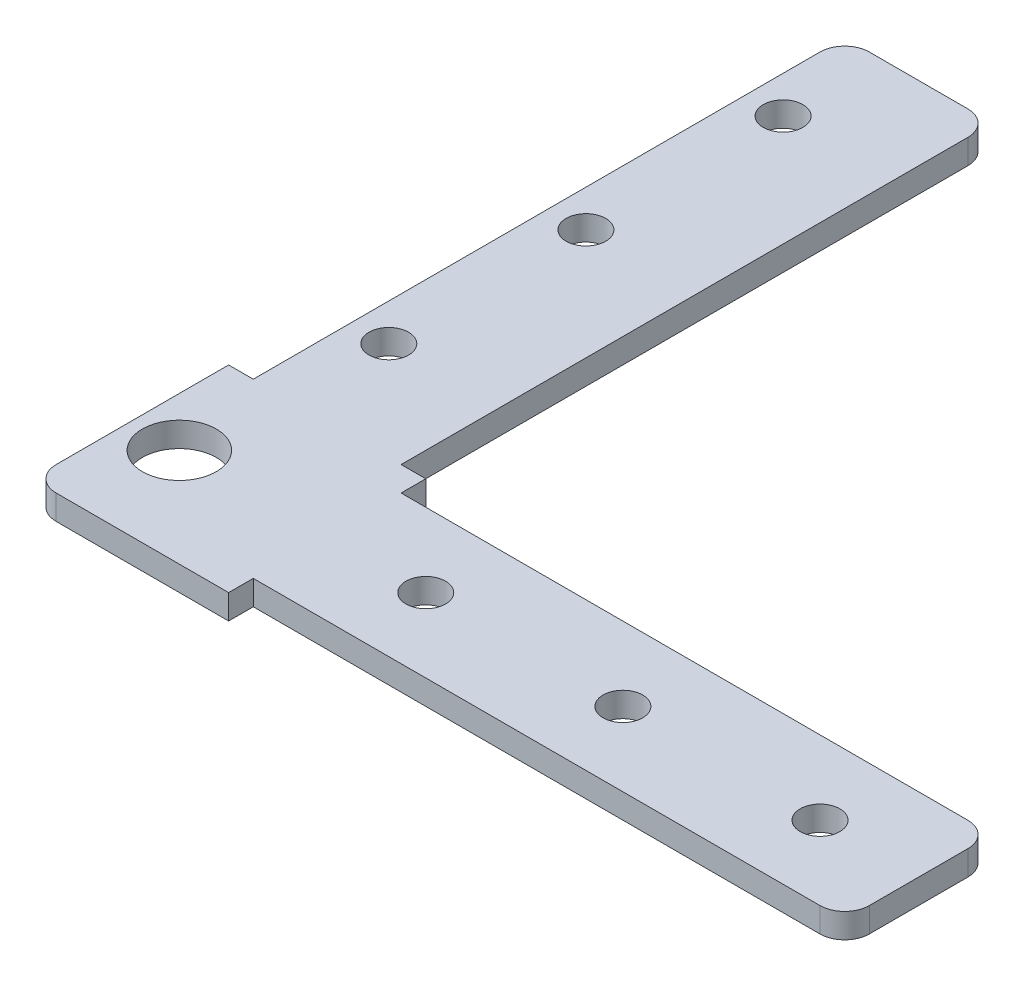
SolidWorks part; units mm, degrees
material "6061 Alloy"
ref_plane "Front" through (0, 0, 0) normal (0, 0, 1) x (1, 0, 0)
ref_plane "Top" through (0, 0, 0) normal (0, 1, 0) x (1, 0, 0)
ref_plane "Right" through (0, 0, 0) normal (1, 0, 0) x (0, 0, -1)
sketch "Sketch2" plane through (0, 0, 0) normal (0, 1, 0) x (1, 0, 0)
  line L0 (0, 0) -> (0, 25.4)
  line L1 (0, 25.4) -> (3.175, 25.4)
  line L2 (3.175, 25.4) -> (3.175, 101.6)
  line L3 (3.175, 101.6) -> (22.225, 101.6)
  line L4 (22.225, 101.6) -> (22.225, 25.4)
  line L5 (22.225, 25.4) -> (25.4, 25.4)
  line L6 (25.4, 25.4) -> (25.4, 22.225)
  line L7 (25.4, 22.225) -> (101.6, 22.225)
  line L8 (101.6, 22.225) -> (101.6, 3.175)
  line L9 (101.6, 3.175) -> (25.4, 3.175)
  line L10 (25.4, 3.175) -> (25.4, 0)
  line L11 (25.4, 0) -> (0, 0)
  dimension "D1" = 25.4
  dimension "D2" = 76.2
  dimension "D3" = 19.05
extrude "Boss-Extrude1" add sketch "Sketch2" along normal blind 3.175
hole_wizard "#10 Clearance Hole1" positions "Sketch3" profile "Sketch4" hole size "#10" standard "ANSI Inch" end condition through all
sketch "Sketch3" plane through (0, 3.175, 0) normal (0, 1, 0) x (1, 0, 0)
  line L0 (7.9375, 101.6) -> (7.9375, 12.7) construction
  line L1 (22.225, 101.6) -> (3.175, 101.6) construction
  line L2 (7.9375, 12.7) -> (101.6, 12.7) construction
  line L3 (101.6, 3.175) -> (101.6, 22.225) construction
  line L5 (0, 25.4) -> (0, 0) construction
  point P10 (7.9375, 88.9)
  point P12 (7.9375, 63.5)
  point P14 (7.9375, 38.1)
  point P16 (38.1, 12.7)
  point P18 (63.5, 12.7)
  point P20 (88.9, 12.7)
  dimension "D1" = 12.7
  dimension "D2" = 25.4
  dimension "D3" = 25.4
  dimension "D4" = 12.7
  dimension "D5" = 25.4
  dimension "D6" = 25.4
  dimension "D7" = 7.9375
sketch "Sketch4" plane through (88.9, 3.175, -12.7) normal (1, 0, 0) x (0, 0, 1)
  line L0 (0, 0) -> (0, 3.175)
  line L1 (0, 3.175) -> (2.5527, 3.175)
  line L2 (2.5527, 3.175) -> (2.5527, 0)
  line L5 (2.5527, 0) -> (0, 0)
  line L11 (0, -6.35) -> (0, 107.95) construction
  dimension "Thru Hole Dia." = 5.1054
  dimension "Thru Hole Depth" = 3.175
sketch "Sketch5" plane through (0, 3.175, 0) normal (0, 1, 0) x (1, 0, 0)
  line L0 (3.175, 25.4) -> (0, 25.4) construction
  line L1 (0, 25.4) -> (0, 0) construction
  circle A0 centre (6.35, 12.7) radius 4.7625
  dimension "D3" = 9.525
  dimension "D1" = 12.7
  dimension "D2" = 6.35
extrude "Cut-Extrude1" cut sketch "Sketch5" against normal through all
fillet "Fillet1" radius 3.175 5 edges at (101.6, 1.5875, -3.175) (101.6, 1.5875, -22.225) (0, 1.5875, 0) (22.225, 1.5875, -101.6) (3.175, 1.5875, -101.6)
hole_wizard "#10 Clearance Hole2" positions "Sketch6" profile "Sketch7" hole size "#10" standard "ANSI Inch"
sketch "Sketch6" plane through (0, 3.175, 0) normal (0, 1, 0) x (1, 0, 0)
  line L0 (7.9375, 38.1) -> (7.9375, 12.7) construction
  line L1 (7.9375, 12.7) -> (38.1, 12.7) construction
  point P2 (7.9375, 12.7)
sketch "Sketch7" plane through (7.9375, 3.175, -12.7) normal (1, 0, 0) x (0, 0, 1)
  line L0 (0, 0) -> (0, 3.175)
  line L1 (0, 3.175) -> (2.5527, 3.175)
  line L2 (2.5527, 3.175) -> (2.5527, 0)
  line L5 (2.5527, 0) -> (0, 0)
  line L11 (0, -6.35) -> (0, 107.95) construction
  dimension "Thru Hole Dia." = 5.1054
  dimension "Thru Hole Depth" = 3.175
